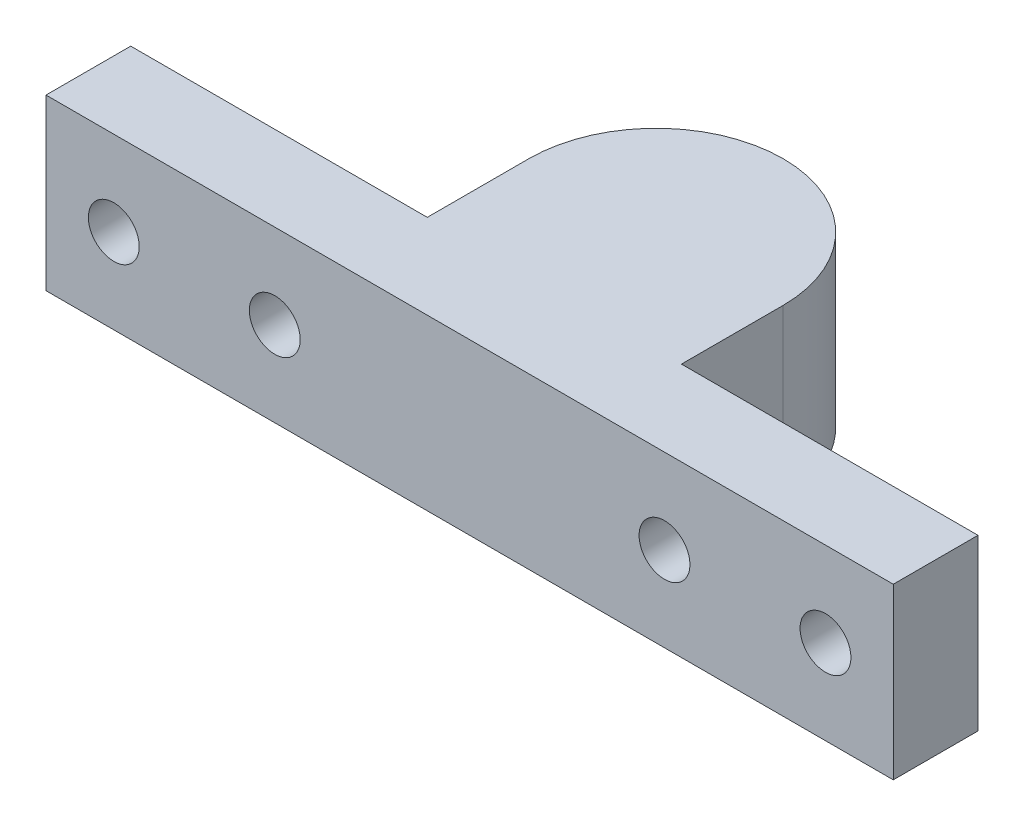
SolidWorks part; units mm, degrees
ref_plane "Płaszczyzna przednia" through (0, 0, 0) normal (0, 0, 1) x (1, 0, 0)
ref_plane "Płaszczyzna górna" through (0, 0, 0) normal (0, 1, 0) x (1, 0, 0)
ref_plane "Płaszczyzna prawa" through (0, 0, 0) normal (1, 0, 0) x (0, 0, -1)
sketch "Szkic1" plane through (0, 0, 0) normal (0, 1, 0) x (1, 0, 0)
  line L0 (-25, 0) -> (25, 0)
  line L1 (-25, 0) -> (-25, 5)
  line L2 (25, 0) -> (25, 5)
  line L3 (25, 5) -> (7.5, 5)
  line L4 (-25, 5) -> (-7.5, 5) construction
  line L5 (25, 5) -> (7.5, 5) construction
  line L6 (-7.5, 5) -> (-7.5, 11)
  line L7 (7.5, 5) -> (7.5, 11)
  line L8 (-7.5, 5) -> (-25, 5)
  arc A0 (-7.5, 11) -> (7.5, 11) centre (0, 11) cw
  point P4 (0, 0)
  dimension "D1" = 50
  dimension "D2" = 5
  dimension "D3" = 5
  dimension "D4" = 17.5
  dimension "D5" = 17.5
  dimension "D6" = 6
  dimension "D7" = 6
extrude "Dodanie-wyciągnięcie1" add sketch "Szkic1" along normal blind 10 contours L2 L3 L7 A0 L6 L8 L1 L0
sketch "Szkic5" plane through (0, 0, -5) normal (0, 0, -1) x (-1, 0, 0)
  line L0 (-25, 5) -> (-22.5, 5) construction
  line L1 (-25, 10) -> (-25, 0) construction
  line L2 (-22.5, 5) -> (-19.5, 5) construction
  line L3 (-19.5, 5) -> (-13, 5) construction
  line L4 (-13, 5) -> (-10, 5) construction
  line L5 (25, 5) -> (21, 5) construction
  line L6 (25, 10) -> (25, 0) construction
  line L7 (25, 5) -> (11.5, 5) construction
  circle A0 centre (-21, 5) radius 1.5
  circle A1 centre (-11.5, 5) radius 1.5
  circle A2 centre (11.5, 5) radius 1.5
  circle A3 centre (21, 5) radius 1.5
  dimension "D7" = 3
  dimension "D8" = 3
  dimension "D1" = 2.5
  dimension "D2" = 3
  dimension "D3" = 6.5
  dimension "D4" = 3
  dimension "D5" = 4
  dimension "D6" = 13.5
extrude "Wytnij-wyciągnięcie2" cut sketch "Szkic5" against normal blind 5
sketch "Szkic6" plane through (0, 0, 0) normal (0, -1, 0) x (1, 0, 0)
  line L0 (0, -18.5) -> (0, -11) construction
  line L2 (-3.9976, -14.9976) -> (3.9976, -14.9976)
  line L3 (-3.9976, -14.9976) -> (-3.9976, -7.0024)
  line L4 (-3.9976, -7.0024) -> (3.9976, -7.0024)
  line L5 (3.9976, -14.9976) -> (3.9976, -7.0024)
  line L6 (-3.9976, -14.9976) -> (3.9976, -7.0024) construction
  line L7 (-3.9976, -7.0024) -> (3.9976, -14.9976) construction
  arc A0 (-7.5, -11) -> (7.5, -11) centre (0, -11) ccw construction
  dimension "D1" = 7.5
  dimension "D2" = 7.9952
extrude "Wytnij-wyciągnięcie3" cut sketch "Szkic6" against normal blind 6.5
